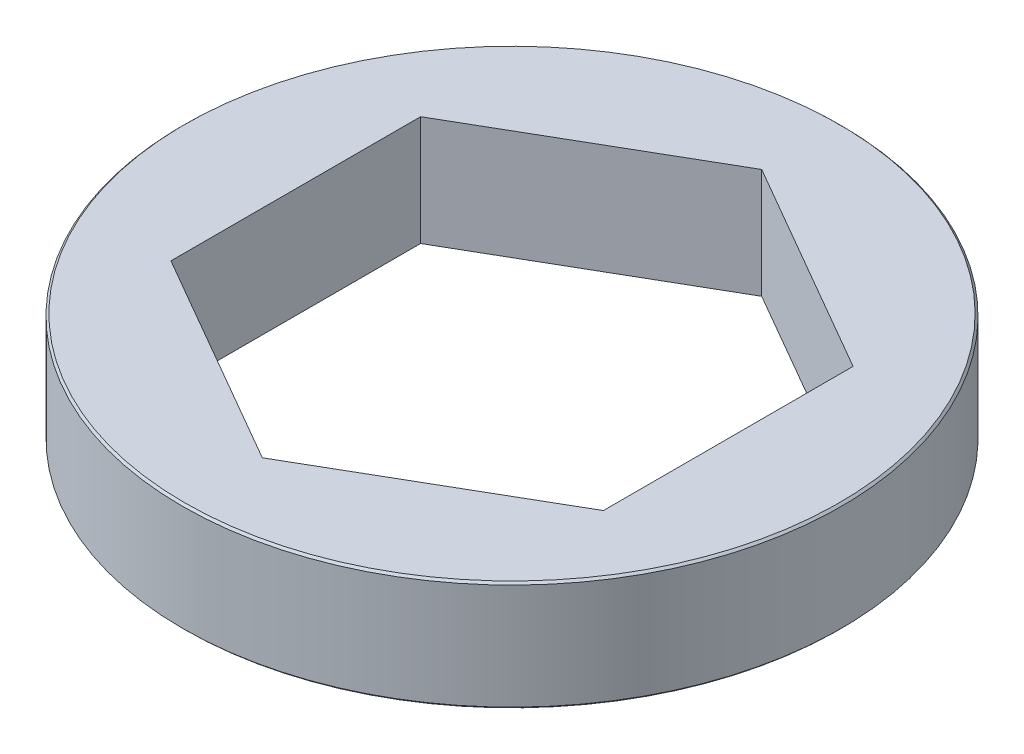
SolidWorks part; units mm, degrees
ref_plane "Front Plane" through (0, 0, 0) normal (0, 0, 1) x (1, 0, 0)
ref_plane "Top Plane" through (0, 0, 0) normal (0, 1, 0) x (1, 0, 0)
ref_plane "Right Plane" through (0, 0, 0) normal (1, 0, 0) x (0, 0, -1)
sketch "Sketch1" plane through (0, 0, 0) normal (0, 1, 0) x (1, 0, 0)
  line L1 (0, 7.2169) -> (-6.25, 3.6084)
  line L2 (-6.25, 3.6084) -> (-6.25, -3.6084)
  line L3 (-6.25, -3.6084) -> (0, -7.2169)
  line L4 (0, -7.2169) -> (6.25, -3.6084)
  line L5 (6.25, -3.6084) -> (6.25, 3.6084)
  line L6 (6.25, 3.6084) -> (0, 7.2169)
  circle A0 centre (0, 0) radius 6.25 construction
  circle A1 centre (0, 0) radius 9.525
  dimension "D1" = 12.5
  dimension "D2" = 19.05
extrude "Boss-Extrude1" add sketch "Sketch1" along normal blind 3.175
chamfer "Chamfer1" distance 0.06 angle 45 1 edges at (0, 0, 9.525)
chamfer "Chamfer2" distance 0.06 angle 45 1 edges at (0, 3.175, 9.525)
